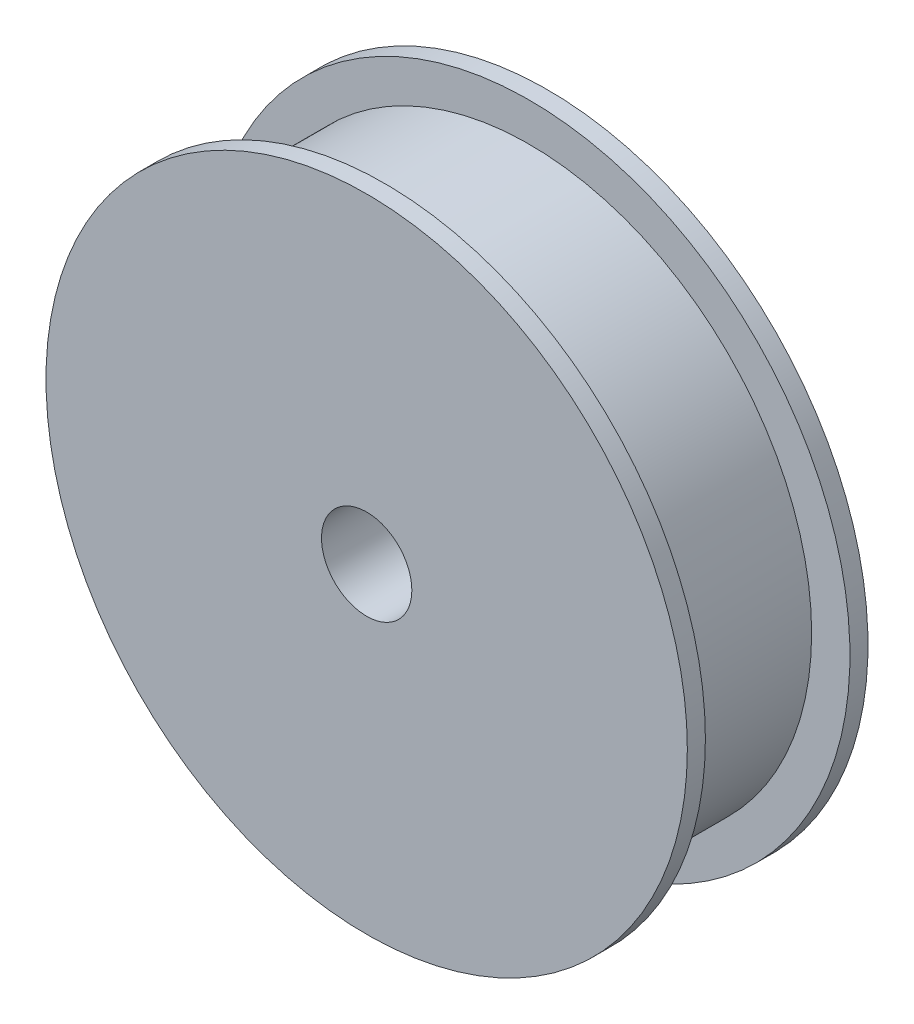
SolidWorks part; units mm, degrees
other "标注1"
sketch "草图5" plane through (35.5, 35.5, 18) normal (0.6094, 0.5558, 0.5655) x (0.4781, 0.3114, -0.8212)
other "细节项目1"
other "细节项目2"
other "标注2"
sketch "草图6" plane through (35.5, -35.5, 18) normal (0.1089, -0.0791, 0.9909) x (0.7576, 0.6519, -0.0313)
other "标注3"
sketch "草图7" plane through (35.5, 35.5, -2) normal (0.575, 0.5795, -0.5775) x (-0.4726, -0.341, -0.8126)
other "细节项目3"
other "细节项目4"
ref_plane "前视基准面" through (0, 0, 0) normal (0, 0, 1) x (1, 0, 0)
ref_plane "上视基准面" through (0, 0, 0) normal (0, 1, 0) x (1, 0, 0)
ref_plane "右视基准面" through (0, 0, 0) normal (1, 0, 0) x (0, 0, -1)
sketch "草图1" plane through (0, 0, 0) normal (0, 0, 1) x (1, 0, 0)
  circle A0 centre (0, 0) radius 31.26
  dimension "D1" = 62.52
extrude "凸台-拉伸1" add sketch "草图1" along normal blind 16 contours A0
sketch "草图2" plane through (0, 0, 16) normal (0, 0, 1) x (1, 0, 0)
  circle A0 centre (0, 0) radius 5
  dimension "D1" = 10
extrude "切除-拉伸1" cut sketch "草图2" against normal blind 16
sketch "草图3" plane through (0, 0, 16) normal (0, 0, 1) x (1, 0, 0)
  circle A0 centre (0, 0) radius 35.5
  circle A1 centre (0, 0) radius 5
  dimension "D1" = 71
extrude "凸台-拉伸2" add sketch "草图3" along normal blind 2
sketch "草图4" plane through (0, 0, 0) normal (0, 0, -1) x (-1, 0, 0)
  circle A0 centre (0, 0) radius 5
  circle A1 centre (0, 0) radius 35.5
  dimension "D1" = 71
extrude "凸台-拉伸3" add sketch "草图4" along normal blind 2
